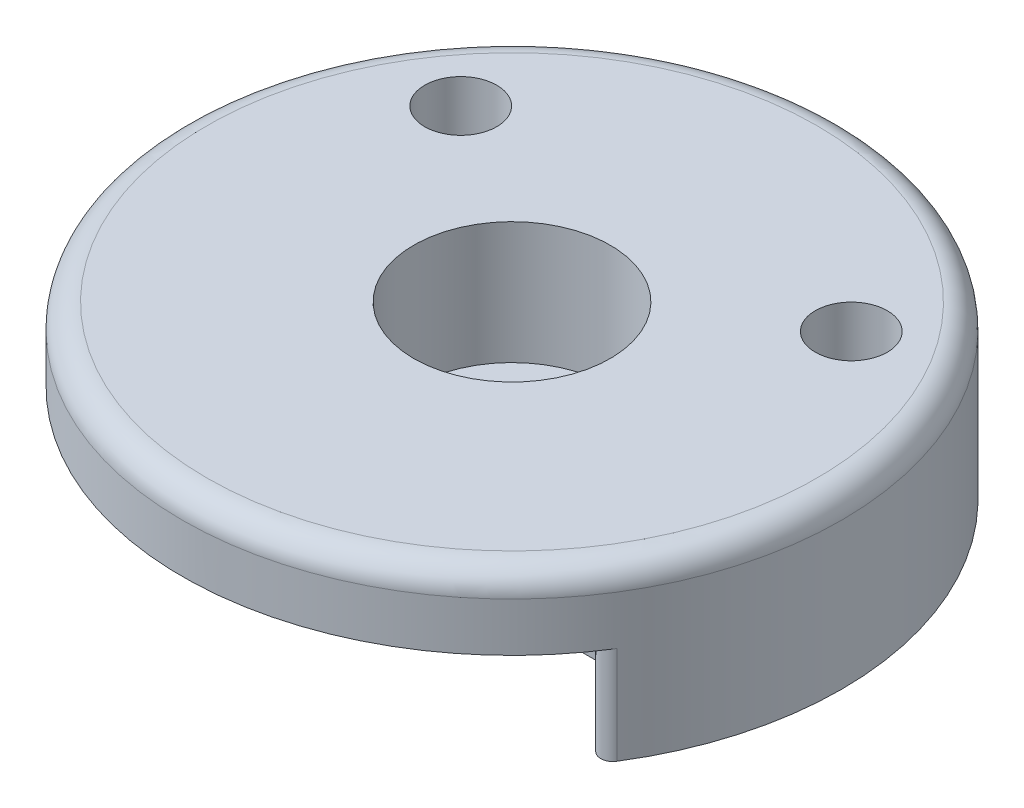
SolidWorks part; units mm, degrees
material "PVC 0.007 Plasticized"
ref_plane "Front Plane" through (0, 0, 0) normal (0, 0, 1) x (1, 0, 0)
ref_plane "Top Plane" through (0, 0, 0) normal (0, 1, 0) x (1, 0, 0)
ref_plane "Right Plane" through (0, 0, 0) normal (1, 0, 0) x (0, 0, -1)
sketch "Sketch2" plane through (0, 0, 0) normal (0, 1, 0) x (1, 0, 0)
  circle A0 centre (0, 0) radius 13.5
  dimension "D1" = 27
extrude "Boss-Extrude1" add sketch "Sketch2" along normal blind 7
sketch "Sketch3" plane through (0, 7, 0) normal (0, 1, 0) x (1, 0, 0)
  circle A0 centre (0, 0) radius 4.025
  dimension "D1" = 8.05
extrude "Cut-Extrude1" cut sketch "Sketch3" against normal blind 5
sketch "Sketch4" plane through (0, 0, 0) normal (0, -1, 0) x (1, 0, 0)
  line L1 (-10.525, 7.85) -> (10.525, 7.85)
  line L2 (-10.525, 7.85) -> (-10.525, -7.85)
  line L3 (-10.525, -7.85) -> (10.525, -7.85)
  line L4 (10.525, 7.85) -> (10.525, -7.85)
  line L5 (-10.525, 7.85) -> (10.525, -7.85) construction
  line L6 (-10.525, -7.85) -> (10.525, 7.85) construction
  point P0 (0, 0)
  dimension "D1" = 15.7
  dimension "D2" = 21.05
extrude "Cut-Extrude2" cut sketch "Sketch4" against normal blind 1
sketch "Sketch5" plane through (0, 1, 0) normal (0, -1, 0) x (1, 0, 0)
  line L0 (-8, -5.9) -> (8, -5.9) construction
  line L1 (10.525, 7.85) -> (-10.525, 7.85) construction
  circle A0 centre (-8, -5.9) radius 1.475
  circle A1 centre (8, -5.9) radius 1.475
  point P4 (0, -5.9)
  dimension "D1" = 2.95
  dimension "D2" = 16
  dimension "D3" = 13.75
extrude "Cut-Extrude3" cut sketch "Sketch5" against normal up to surface (6 mm away) up to face at (0, 7, 4.025)
fillet "Fillet1" radius 1 1 edges at (0, 7, 13.5)
sketch "Sketch6" plane through (0, 1, 0) normal (0, -1, 0) x (1, 0, 0)
  line L0 (10.525, -7.85) -> (10.525, 7.85) construction
  line L1 (10.525, 5) -> (-10.525, 5)
  line L2 (10.525, 5) -> (10.525, 13.5)
  line L3 (10.525, 13.5) -> (-10.525, 13.5)
  line L4 (-10.525, 5) -> (-10.525, 13.5)
  line L5 (-10.525, 7.85) -> (-10.525, -7.85) construction
  circle A0 centre (0, 0) radius 13.5 construction
  dimension "D1" = 5
extrude "Cut-Extrude5" cut sketch "Sketch6" against normal blind 3 and the other way up to surface (1 mm away) other way up to face at (0, 0, 0)
fillet "Fillet2" radius 0.5 2 edges at (10.525, 2, 8.4543) (-10.525, 2, 8.4543)
